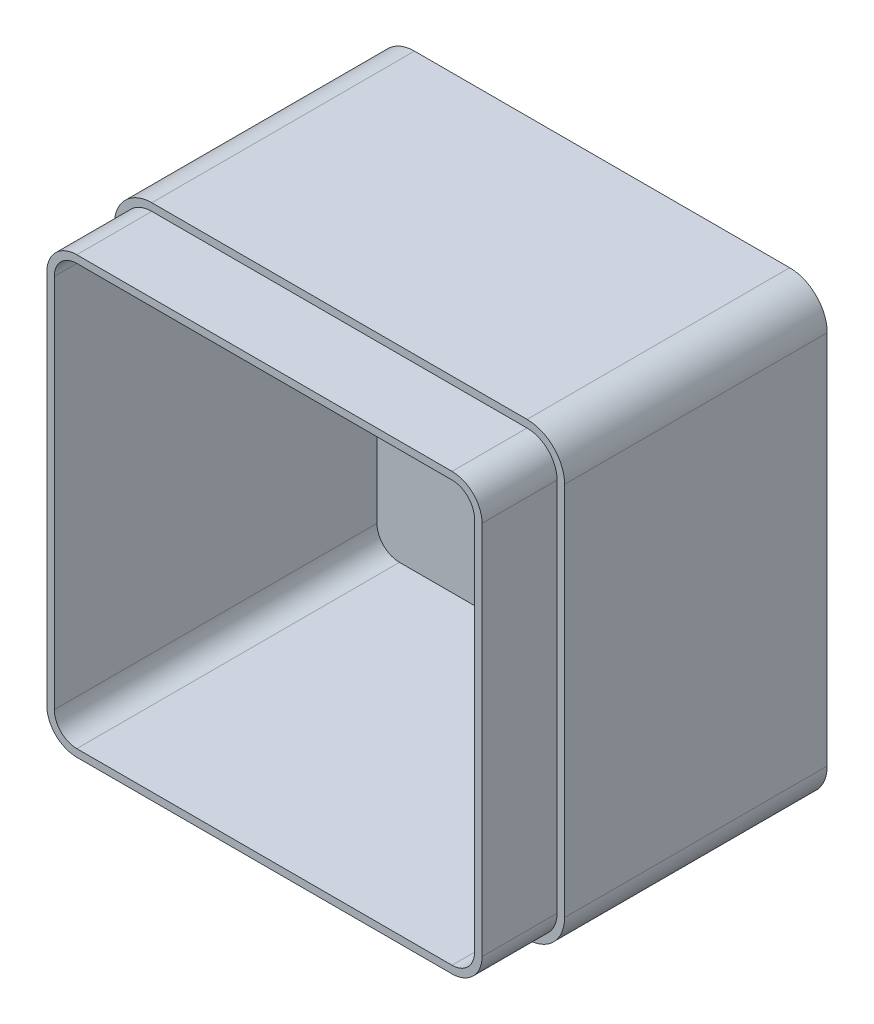
SolidWorks part; units mm, degrees
ref_plane "Front Plane" through (0, 0, 0) normal (0, 0, 1) x (1, 0, 0)
ref_plane "Top Plane" through (0, 0, 0) normal (0, 1, 0) x (1, 0, 0)
ref_plane "Right Plane" through (0, 0, 0) normal (1, 0, 0) x (0, 0, -1)
sketch "Sketch1" plane through (0, 0, 0) normal (0, 0, 1) x (1, 0, 0)
  line L1 (0, 0) -> (120, 0)
  line L2 (0, 0) -> (0, 120)
  line L3 (0, 120) -> (120, 120)
  line L4 (120, 0) -> (120, 120)
  dimension "D1" = 120
  dimension "D2" = 120
extrude "Boss-Extrude1" add sketch "Sketch1" along normal blind 90
fillet "Fillet1" radius 10 4 edges at (0, 0, 45) (0, 120, 45) (120, 0, 45) (120, 120, 45)
shell "Shell1" thickness 4
sketch "Sketch2" plane through (0, 0, 90) normal (0, 0, 1) x (1, 0, 0)
  line L0 (2, 110) -> (2, 10)
  line L1 (10, 2) -> (110, 2)
  line L2 (118, 10) -> (118, 110)
  line L3 (110, 118) -> (10, 118)
  line L4 (0, 110) -> (0, 10)
  line L5 (10, 0) -> (110, 0)
  line L6 (120, 10) -> (120, 110)
  line L7 (110, 120) -> (10, 120)
  line L8 (0, 110) -> (0, 10)
  line L9 (10, 0) -> (110, 0)
  line L10 (120, 10) -> (120, 110)
  line L11 (110, 120) -> (10, 120)
  arc A0 (2, 10) -> (10, 2) centre (10, 10) ccw
  arc A1 (110, 2) -> (118, 10) centre (110, 10) ccw
  arc A2 (118, 110) -> (110, 118) centre (110, 110) ccw
  arc A3 (10, 118) -> (2, 110) centre (10, 110) ccw
  arc A4 (0, 10) -> (10, 0) centre (10, 10) ccw
  arc A5 (110, 0) -> (120, 10) centre (110, 10) ccw
  arc A6 (120, 110) -> (110, 120) centre (110, 110) ccw
  arc A7 (10, 120) -> (0, 110) centre (10, 110) ccw
  arc A8 (0, 10) -> (10, 0) centre (10, 10) ccw
  arc A9 (110, 0) -> (120, 10) centre (110, 10) ccw
  arc A10 (120, 110) -> (110, 120) centre (110, 110) ccw
  arc A11 (10, 120) -> (0, 110) centre (10, 110) ccw
  dimension "D1" = 0
  dimension "D2" = 2
extrude "Cut-Extrude1" cut sketch "Sketch2" against normal blind 20
